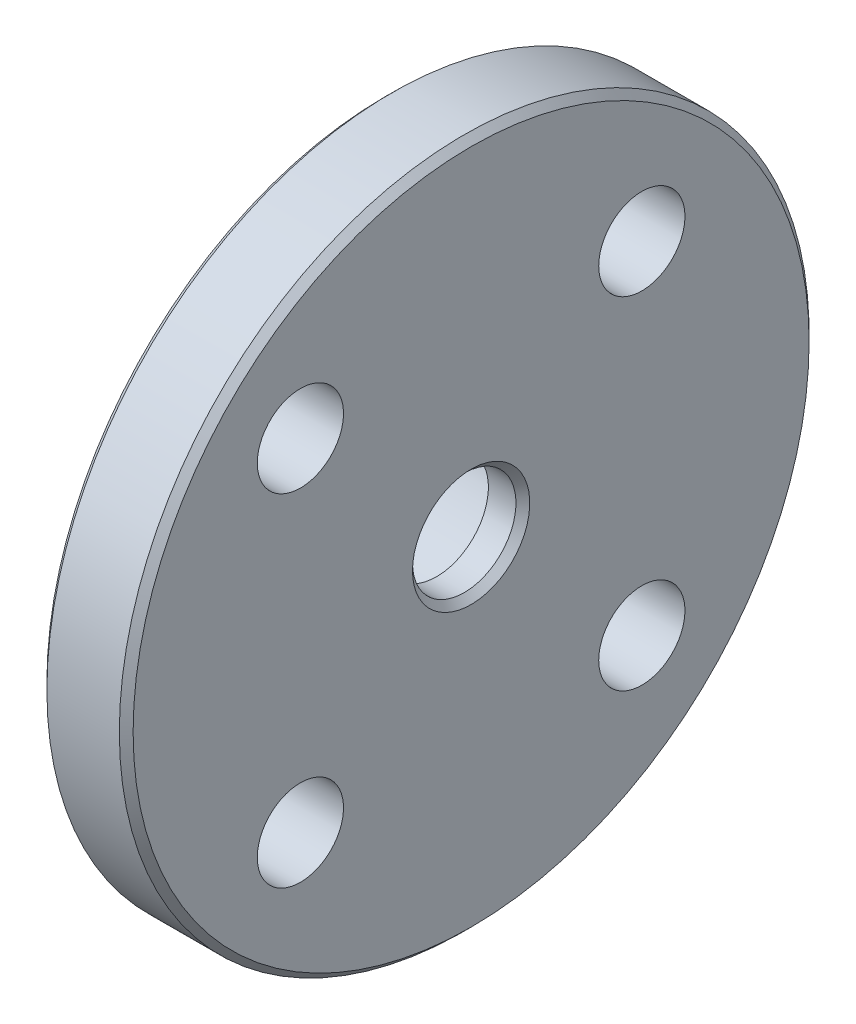
SolidWorks part; units mm, degrees
ref_plane "前视基准面" through (0, 0, 0) normal (0, 0, 1) x (1, 0, 0)
ref_plane "上视基准面" through (0, 0, 0) normal (0, 1, 0) x (1, 0, 0)
ref_plane "右视基准面" through (0, 0, 0) normal (1, 0, 0) x (0, 0, -1)
sketch "草图2" plane through (0, 0, 0) normal (0, 0, 1) x (1, 0, 0)
  line L0 (0, 3) -> (0, 4.5)
  line L1 (0, 4.5) -> (2, 4.5)
  line L2 (2, 4.5) -> (2, 10)
  line L3 (2, 10) -> (4.5, 10)
  line L4 (4.5, 10) -> (4.5, 1.5)
  line L5 (4.5, 1.5) -> (3.5, 1.5)
  line L6 (3.5, 1.5) -> (3.5, 3)
  line L7 (3.5, 3) -> (0, 3)
  line L8 (0, 0) -> (5.26, 0) construction
  dimension "D1" = 1
  dimension "D2" = 3.5
  dimension "D3" = 2.5
  dimension "D4" = 20
  dimension "D5" = 9
  dimension "D6" = 6
  dimension "D7" = 3
revolve "旋转1" add sketch "草图2" angle 360 about L8
sketch "草图3" plane through (2, 0, 0) normal (-1, 0, 0) x (0, 0, 1)
  line L0 (0, 0) -> (10, 0) construction
  line L1 (0, 0) -> (7.0711, 7.0711) construction
  circle A0 centre (0, 0) radius 10 construction
  circle A1 centre (4.9497, 4.9497) radius 1.25
  circle A2 centre (4.9497, -4.9497) radius 1.25
  circle A3 centre (-4.9497, -4.9497) radius 1.25
  circle A4 centre (-4.9497, 4.9497) radius 1.25
  point P18 (0, 0)
  dimension "D2" = 2.5
  dimension "D3" = 7
  dimension "D1" = 45
  dimension "D4" = 4
extrude "切除-拉伸1" cut sketch "草图3" against normal through all
chamfer "倒角1" distance 0.2 angle 45 4 edges at (4.5, 0, 1.5) (4.5, 0, 10) (2, 0, 10) (0, 0, 4.5)
move or copy body "实体-移动/复制1" [suppressed] bodies to move or copy 107
